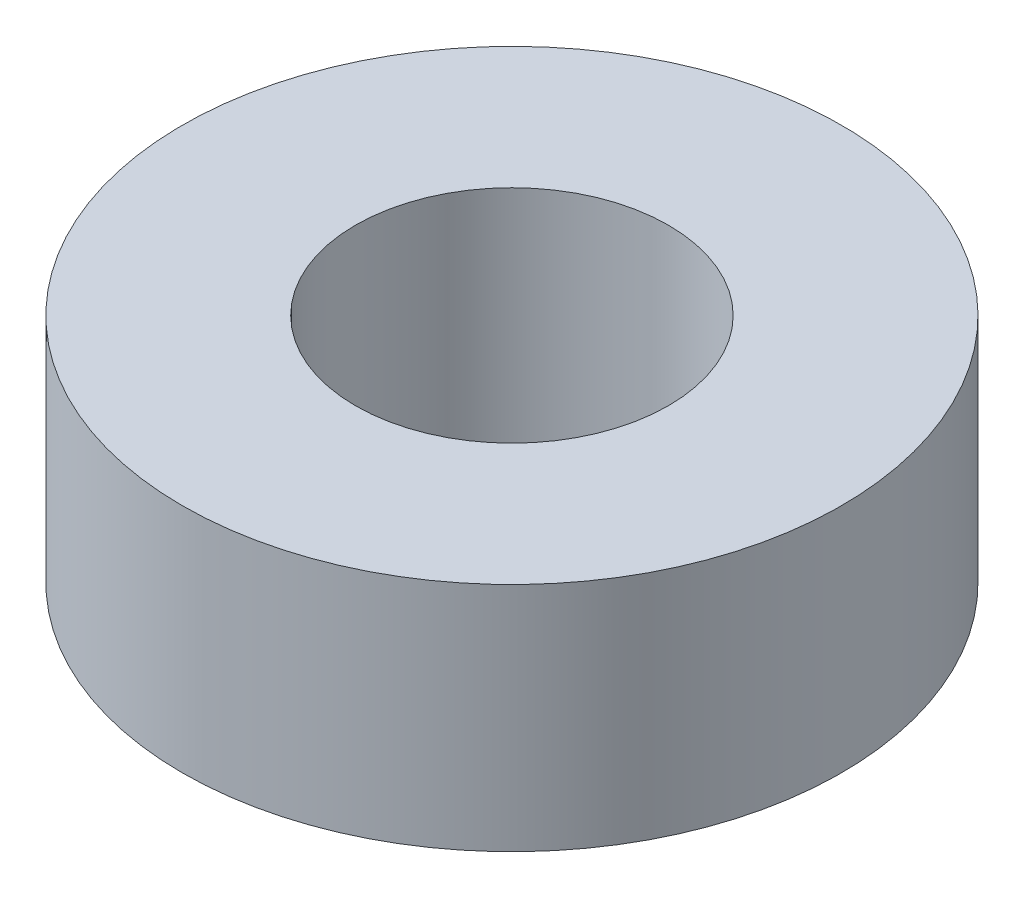
SolidWorks part; units mm, degrees
ref_plane "Front Plane" through (0, 0, 0) normal (0, 0, 1) x (1, 0, 0)
ref_plane "Top Plane" through (0, 0, 0) normal (0, 1, 0) x (1, 0, 0)
ref_plane "Right Plane" through (0, 0, 0) normal (1, 0, 0) x (0, 0, -1)
sketch "Sketch1" plane through (0, 0, 0) normal (0, 1, 0) x (1, 0, 0)
  circle A0 centre (0, 0) radius 12.36
  dimension "D1" = 24.72
extrude "Boss-Extrude1" add sketch "Sketch1" along normal blind 8.678
sketch "Sketch2" plane through (0, 0, 0) normal (0, -1, 0) x (-1, 0, 0)
  circle A0 centre (0, 0) radius 5.8674
  dimension "D1" = 11.7348
extrude "Cut-Extrude1" cut sketch "Sketch2" against normal through all
sketch "Sketch4" plane through (0, 8.678, 0) normal (0, 1, 0) x (1, 0, 0)
  circle A0 centre (0, 0) radius 12.0429 construction
  text T0 "<b>1mm</b>" font "Cambria" height 5.08
extrude "Cut-Extrude2" [suppressed] cut sketch "Sketch4" against normal blind 0.2
